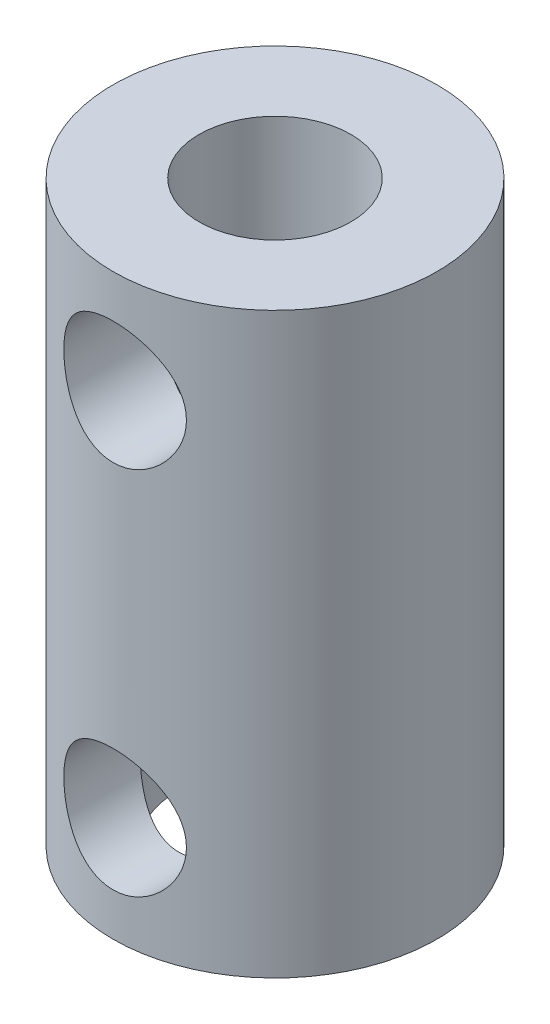
SolidWorks part; units mm, degrees
ref_plane "Front Plane" through (0, 0, 0) normal (0, 0, 1) x (1, 0, 0)
ref_plane "Top Plane" through (0, 0, 0) normal (0, 1, 0) x (1, 0, 0)
ref_plane "Right Plane" through (0, 0, 0) normal (1, 0, 0) x (0, 0, -1)
sketch "Sketch1" plane through (0, 0, 0) normal (0, 0, 1) x (1, 0, 0)
  line L0 (5.334, 19.05) -> (0, 19.05)
  line L1 (0, 19.05) -> (0, 0)
  line L2 (0, 0) -> (5.334, 0)
  line L3 (5.334, 0) -> (5.334, 19.05)
  line L4 (0, 19.05) -> (0, 0) construction
revolve "Revolve1" add sketch "Sketch1" angle 360 about L4
hole_wizard "Hole1" positions "Sketch3" profile "Sketch2" legacy
sketch "Sketch3" plane through (0, 0, 0) normal (0, -1, 0) x (-1, 0, 0)
  point P0 (0, 0)
sketch "Sketch2" plane through (0, 0, 0) normal (1, 0, 0) x (0, 0, -1)
  line L0 (0, 0) -> (0, 19.05)
  line L1 (0, 19.05) -> (2.5, 19.05)
  line L2 (2.5, 19.05) -> (2.5, 9.9306)
  line L3 (2.5, 9.9306) -> (3.175, 9.525)
  line L4 (3.175, 9.525) -> (3.175, 0)
  line L5 (3.175, 0) -> (0, 0)
  line L6 (0, -6.13) -> (0, 109.2824) construction
  line L7 (-2.5, 9.9306) -> (-3.175, 9.525) construction
  line L8 (0, 19.05) -> (-2.5, 19.05) construction
  dimension "Diameter" = 5
  dimension "Depth" = 19.05
  dimension "C-Drill Diameter" = 6.35
  dimension "C-Drill Depth" = 9.525
  dimension "C-Drill Angle" = 118
hole_wizard "M3.5 Clearance Hole1" positions "3DSketch1" profile "Sketch4" hole size "M3.5" standard "ANSI Metric"
sketch3d "3DSketch1"
  point P0 (0, 15.621, 5.334)
sketch "Sketch4" plane through (0, 15.621, 5.334) normal (1, 0, 0) x (0, -1, 0)
  line L0 (0, 0) -> (0, 2.834)
  line L1 (0, 2.834) -> (2.0193, 2.834)
  line L2 (2.0193, 2.834) -> (2.0193, 0)
  line L5 (2.0193, 0) -> (0, 0)
  line L11 (0, -6.35) -> (0, 107.95) construction
  dimension "Thru Hole Dia." = 4.0386
  dimension "Thru Hole Depth" = 2.834
hole_wizard "M3.5 Clearance Hole2" positions "3DSketch2" profile "Sketch5" hole size "M3.5" standard "ANSI Metric"
sketch3d "3DSketch2"
  point P0 (0, 3.429, 5.334)
sketch "Sketch5" plane through (0, 3.429, 5.334) normal (1, 0, 0) x (0, -1, 0)
  line L0 (0, 0) -> (0, 2.159)
  line L1 (0, 2.159) -> (2.0193, 2.159)
  line L2 (2.0193, 2.159) -> (2.0193, 0)
  line L5 (2.0193, 0) -> (0, 0)
  line L11 (0, -6.35) -> (0, 107.95) construction
  dimension "Thru Hole Dia." = 4.0386
  dimension "Thru Hole Depth" = 2.159
